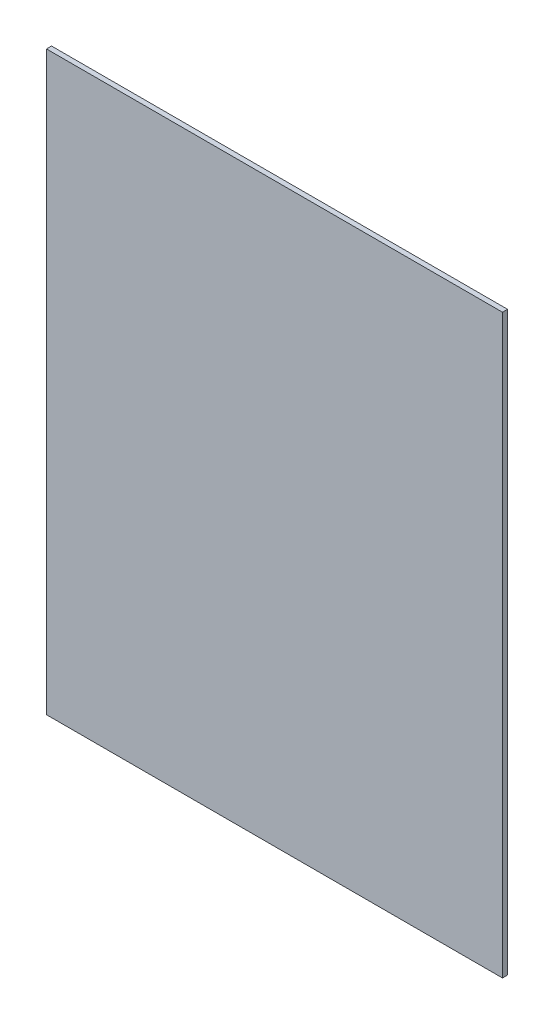
SolidWorks part; units mm, degrees
material "Acrylic"
ref_plane "Front Plane" through (0, 0, 0) normal (0, 0, 1) x (1, 0, 0)
ref_plane "Top Plane" through (0, 0, 0) normal (0, 1, 0) x (1, 0, 0)
ref_plane "Right Plane" through (0, 0, 0) normal (1, 0, 0) x (0, 0, -1)
sketch "Sketch1" plane through (0, 0, 0) normal (0, 0, 1) x (1, 0, 0)
  line L1 (-36.2493, 1028.8289) -> (822.5247, 1028.8289)
  line L2 (-36.2493, 1028.8289) -> (-36.2493, -57.0211)
  line L3 (-36.2493, -57.0211) -> (822.5247, -57.0211)
  line L4 (822.5247, 1028.8289) -> (822.5247, -57.0211)
  dimension "D1" = 1085.85
  dimension "D2" = 858.774
extrude "Boss-Extrude1" add sketch "Sketch1" along normal blind 9.525 contours L2 L1 L4 L3
